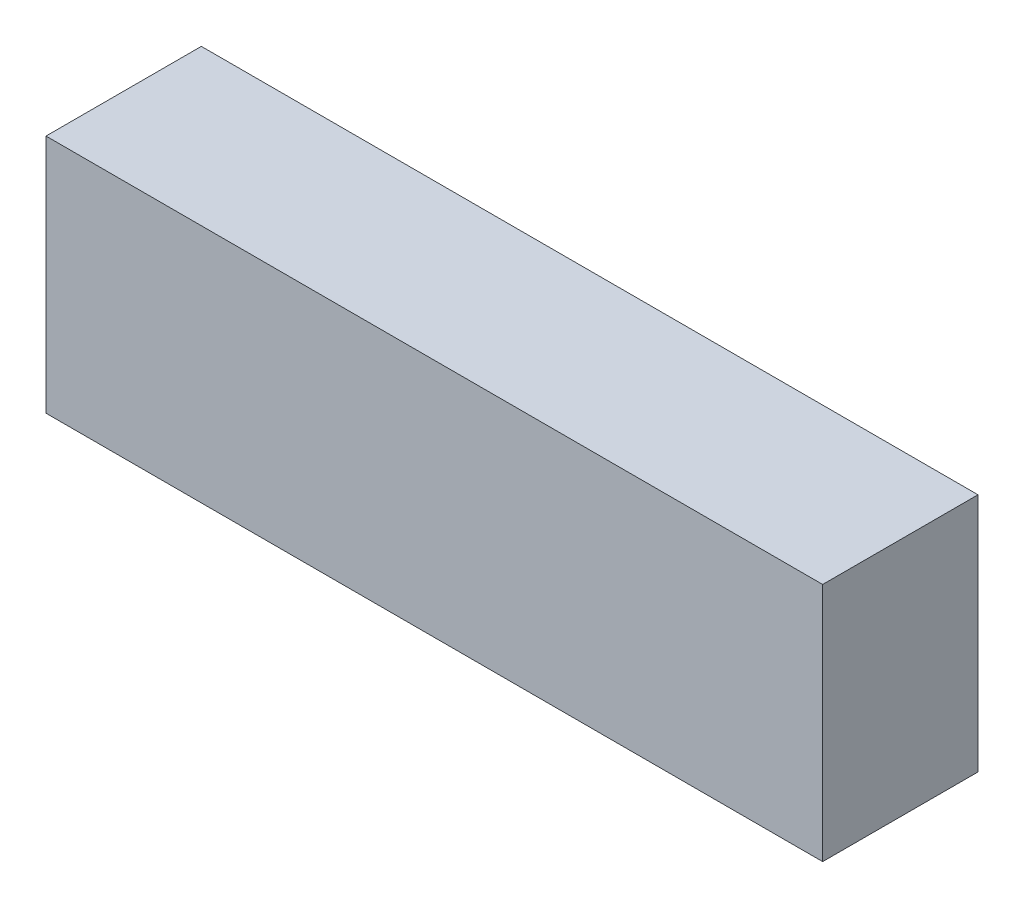
SolidWorks part; units mm, degrees
ref_plane "Front Plane" through (0, 0, 0) normal (0, 0, 1) x (1, 0, 0)
ref_plane "Top Plane" through (0, 0, 0) normal (0, 1, 0) x (1, 0, 0)
ref_plane "Right Plane" through (0, 0, 0) normal (1, 0, 0) x (0, 0, -1)
sketch "Sketch1" plane through (0, 0, 0) normal (0, 0, 1) x (1, 0, 0)
  line L1 (-55, -17) -> (55, -17)
  line L2 (-55, -17) -> (-55, 17)
  line L3 (-55, 17) -> (55, 17)
  line L4 (55, -17) -> (55, 17)
  line L5 (-55, -17) -> (55, 17) construction
  line L6 (-55, 17) -> (55, -17) construction
  point P0 (0, 0)
  dimension "D1" = 34
  dimension "D2" = 110
extrude "Boss-Extrude1" add sketch "Sketch1" along normal blind 22
